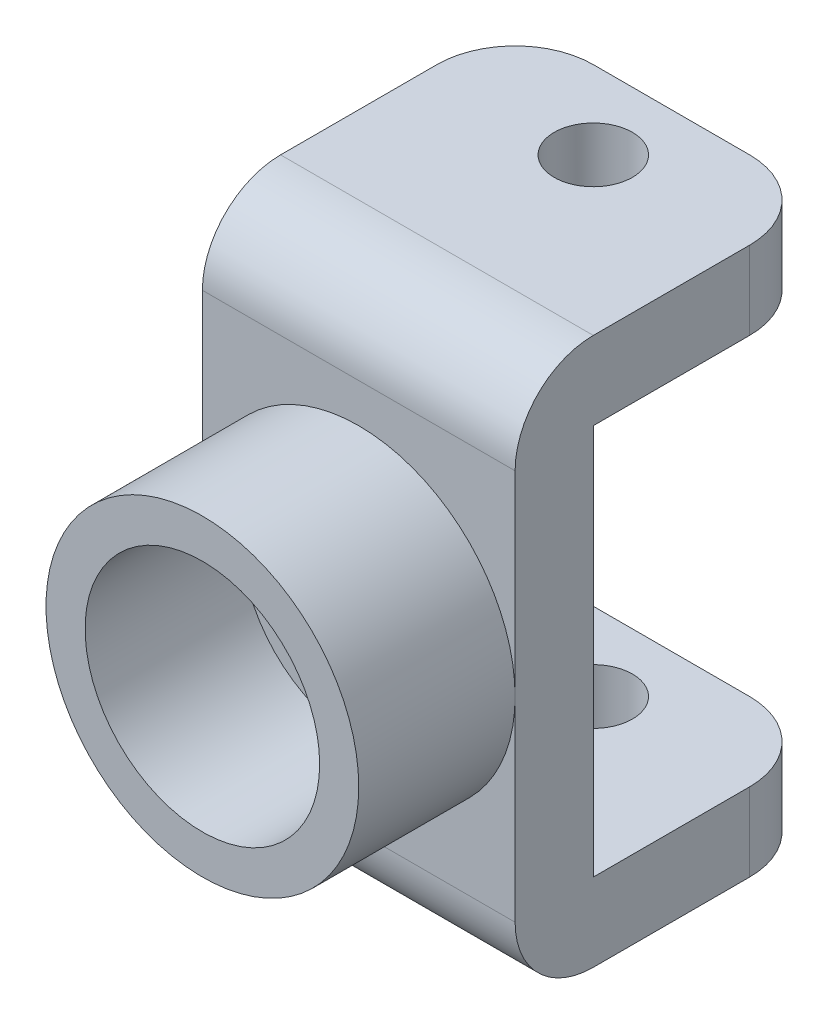
SolidWorks part; units mm, degrees
ref_plane "Front Plane" through (0, 0, 0) normal (0, 0, 1) x (1, 0, 0)
ref_plane "Top Plane" through (0, 0, 0) normal (0, 1, 0) x (1, 0, 0)
ref_plane "Right Plane" through (0, 0, 0) normal (1, 0, 0) x (0, 0, -1)
sketch "Sketch1" plane through (0, 0, 0) normal (0, 0, 1) x (1, 0, 0)
  line L1 (-20, 25) -> (20, 25)
  line L2 (-20, 25) -> (-20, -25)
  line L3 (-20, -25) -> (20, -25)
  line L4 (20, 25) -> (20, -25)
  line L5 (-20, 25) -> (20, -25) construction
  line L6 (-20, -25) -> (20, 25) construction
  point P0 (0, 0)
  dimension "D1" = 40
  dimension "D2" = 50
extrude "Boss-Extrude1" add sketch "Sketch1" along normal blind 10
sketch "Sketch2" plane through (0, 0, 0) normal (1, 0, 0) x (0, 0, -1)
  line L1 (-10, 25) -> (30, 25)
  line L2 (-10, 25) -> (-10, 35)
  line L3 (-10, 35) -> (30, 35)
  line L4 (30, 25) -> (30, 35)
  line L5 (-10, -25) -> (30, -25)
  line L6 (-10, -25) -> (-10, -35)
  line L7 (-10, -35) -> (30, -35)
  line L8 (30, -25) -> (30, -35)
  dimension "D1" = 10
  dimension "D2" = 10
  dimension "D3" = 40
  dimension "D4" = 40
extrude "Boss-Extrude2" add sketch "Sketch2" along normal mid plane 40
fillet "Fillet1" radius 10 6 edges at (0, -35, 10) (-20, -30, -30) (20, -30, -30) (-20, 30, -30) (0, 35, 10) (20, 30, -30)
sketch "Sketch3" plane through (0, 0, 10) normal (0, 0, 1) x (1, 0, 0)
  circle A0 centre (0, 0) radius 20
  circle A1 centre (0, 0) radius 15
  dimension "D1" = 30
extrude "Boss-Extrude3" add sketch "Sketch3" along normal blind 20
sketch "Sketch4" plane through (0, -35, 0) normal (0, -1, 0) x (1, 0, 0)
  line L0 (0, -30) -> (0, -20)
  line L1 (10, -30) -> (-10, -30) construction
  circle A0 centre (0, -20) radius 5
  dimension "D2" = 10
  dimension "D1" = 10
extrude "Cut-Extrude1" cut sketch "Sketch4" against normal through all
